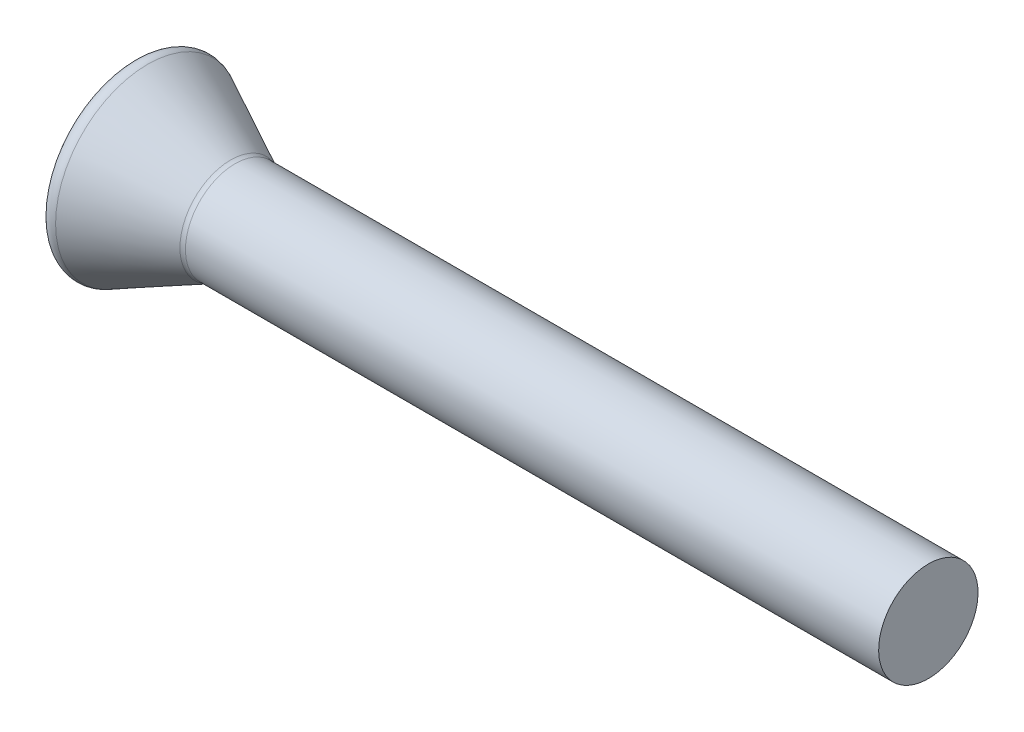
SolidWorks part; units mm, degrees
ref_plane "前视基准面" through (0, 0, 0) normal (0, 0, 1) x (1, 0, 0)
ref_plane "上视基准面" through (0, 0, 0) normal (0, 1, 0) x (1, 0, 0)
ref_plane "右视基准面" through (0, 0, 0) normal (1, 0, 0) x (0, 0, -1)
sketch "草图1" plane through (0, 0, 0) normal (0, 0, 1) x (1, 0, 0)
  line L0 (0, 0) -> (0, 1)
  line L1 (0, 1) -> (1, 0.5)
  line L2 (1, 0.5) -> (8, 0.5)
  line L3 (8, 0.5) -> (8, 0)
  line L4 (8, 0) -> (0, 0)
  dimension "D1" = 1
  dimension "D2" = 0.5
  dimension "D3" = 8
  dimension "D4" = 1
revolve "旋转1" add sketch "草图1" angle 360 about L4
cosmetic thread "装饰螺纹线1" parameters "D2"=0.9
fillet "圆角1" radius 0.1 2 edges at (1, 0.5, 0) (0, 1, 0)
